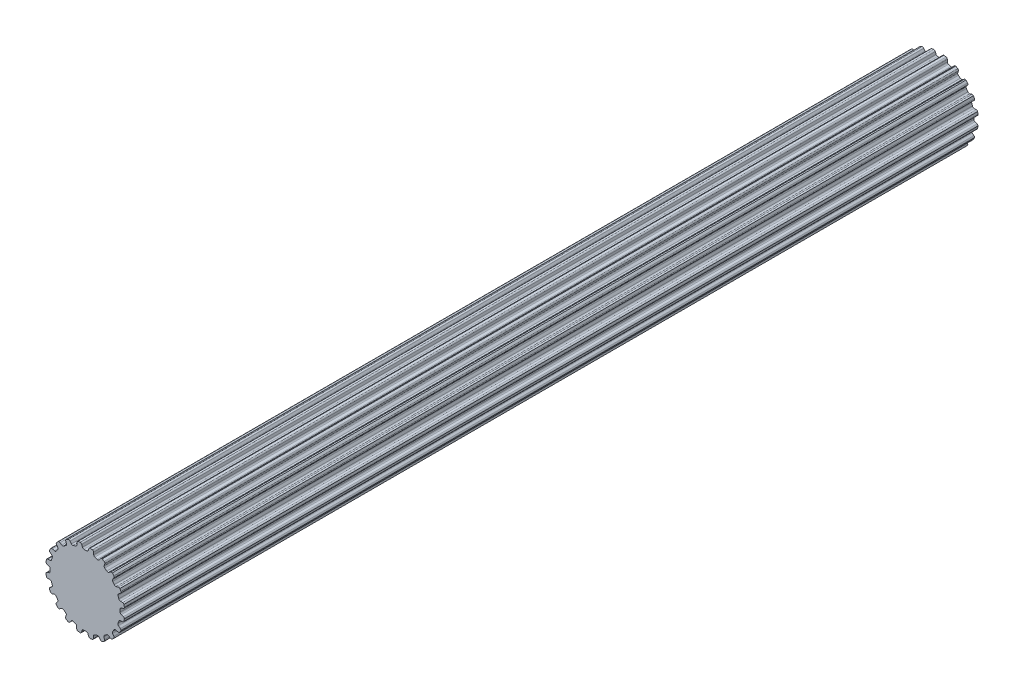
SolidWorks part; units mm, degrees
ref_plane "Front Plane" through (0, 0, 0) normal (0, 0, 1) x (1, 0, 0)
ref_plane "Top Plane" through (0, 0, 0) normal (0, 1, 0) x (1, 0, 0)
ref_plane "Right Plane" through (0, 0, 0) normal (1, 0, 0) x (0, 0, -1)
sketch "Sketch1" plane through (0, 0, 0) normal (0, 0, 1) x (1, 0, 0)
  line L0 (-0.1069, 2.9699) -> (0.1069, 2.9699)
  line L1 (0.3159, 3.2375) -> (0.2537, 3.0575)
  line L2 (-0.2964, 3.2367) -> (-0.2318, 3.0575)
  line L3 (-0.2964, 3.2367) -> (0.3159, 3.2375) construction
  line L4 (0, 3.3252) -> (0, 0) construction
  line L5 (-0.2318, 3.0575) -> (0.2537, 3.0575) construction
  line L6 (-0.4281, 3.3241) -> (0.4281, 3.3263) construction
  line L7 (0.7183, 3.1698) -> (0.7244, 2.9795)
  line L8 (0.816, 2.8576) -> (1.0195, 2.7915)
  line L9 (1.3009, 2.9815) -> (1.1862, 2.8295)
  line L10 (1.6627, 2.7927) -> (1.6097, 2.6099)
  line L11 (1.6591, 2.4655) -> (1.8322, 2.3398)
  line L12 (2.1585, 2.4335) -> (2.0025, 2.3245)
  line L13 (2.4443, 2.1423) -> (2.3374, 1.9847)
  line L14 (2.3398, 1.8322) -> (2.4655, 1.6591)
  line L15 (2.8049, 1.6474) -> (2.6228, 1.5919)
  line L16 (2.9866, 1.2821) -> (2.8363, 1.1653)
  line L17 (2.7915, 1.0195) -> (2.8576, 0.816)
  line L18 (3.1767, 0.7) -> (2.9863, 0.7035)
  line L19 (3.2367, 0.2964) -> (3.0575, 0.2318)
  line L20 (2.9699, 0.1069) -> (2.9699, -0.1069)
  line L21 (3.2375, -0.3159) -> (3.0575, -0.2537)
  line L22 (3.1698, -0.7183) -> (2.9795, -0.7244)
  line L23 (2.8576, -0.816) -> (2.7915, -1.0195)
  line L24 (2.9815, -1.3009) -> (2.8295, -1.1862)
  line L25 (2.7927, -1.6627) -> (2.6099, -1.6097)
  line L26 (2.4655, -1.6591) -> (2.3398, -1.8322)
  line L27 (2.4335, -2.1585) -> (2.3245, -2.0025)
  line L28 (2.1423, -2.4443) -> (1.9847, -2.3374)
  line L29 (1.8322, -2.3398) -> (1.6591, -2.4655)
  line L30 (1.6474, -2.8049) -> (1.5919, -2.6228)
  line L31 (1.2821, -2.9866) -> (1.1653, -2.8363)
  line L32 (1.0195, -2.7915) -> (0.816, -2.8576)
  line L33 (0.7, -3.1767) -> (0.7035, -2.9863)
  line L34 (0.2964, -3.2367) -> (0.2318, -3.0575)
  line L35 (0.1069, -2.9699) -> (-0.1069, -2.9699)
  line L36 (-0.3159, -3.2375) -> (-0.2537, -3.0575)
  line L37 (-0.7183, -3.1698) -> (-0.7244, -2.9795)
  line L38 (-0.816, -2.8576) -> (-1.0195, -2.7915)
  line L39 (-1.3009, -2.9815) -> (-1.1862, -2.8295)
  line L40 (-1.6627, -2.7927) -> (-1.6097, -2.6099)
  line L41 (-1.6591, -2.4655) -> (-1.8322, -2.3398)
  line L42 (-2.1585, -2.4335) -> (-2.0025, -2.3245)
  line L43 (-2.4443, -2.1423) -> (-2.3374, -1.9847)
  line L44 (-2.3398, -1.8322) -> (-2.4655, -1.6591)
  line L45 (-2.8049, -1.6474) -> (-2.6228, -1.5919)
  line L46 (-2.9866, -1.2821) -> (-2.8363, -1.1653)
  line L47 (-2.7915, -1.0195) -> (-2.8576, -0.816)
  line L48 (-3.1767, -0.7) -> (-2.9863, -0.7035)
  line L49 (-3.2367, -0.2964) -> (-3.0575, -0.2318)
  line L50 (-2.9699, -0.1069) -> (-2.9699, 0.1069)
  line L51 (-3.2375, 0.3159) -> (-3.0575, 0.2537)
  line L52 (-3.1698, 0.7183) -> (-2.9795, 0.7244)
  line L53 (-2.8576, 0.816) -> (-2.7915, 1.0195)
  line L54 (-2.9815, 1.3009) -> (-2.8295, 1.1862)
  line L55 (-2.7927, 1.6627) -> (-2.6099, 1.6097)
  line L56 (-2.4655, 1.6591) -> (-2.3398, 1.8322)
  line L57 (-2.4335, 2.1585) -> (-2.3245, 2.0025)
  line L58 (-2.1423, 2.4443) -> (-1.9847, 2.3374)
  line L59 (-1.8322, 2.3398) -> (-1.6591, 2.4655)
  line L60 (-1.6474, 2.8049) -> (-1.5919, 2.6228)
  line L61 (-1.2821, 2.9866) -> (-1.1653, 2.8363)
  line L62 (-1.0195, 2.7915) -> (-0.816, 2.8576)
  line L63 (-0.7, 3.1767) -> (-0.7035, 2.9863)
  line L64 (0.4281, 3.3263) -> (0.62, 3.2938)
  line L65 (1.4351, 3.0312) -> (1.6075, 2.9409)
  line L66 (2.3015, 2.4394) -> (2.4376, 2.3003)
  line L67 (2.9427, 1.6088) -> (3.0291, 1.4344)
  line L68 (3.2958, 0.6207) -> (3.3241, 0.4281)
  line L69 (3.3263, -0.4281) -> (3.2938, -0.62)
  line L70 (3.0312, -1.4351) -> (2.9409, -1.6075)
  line L71 (2.4394, -2.3015) -> (2.3003, -2.4376)
  line L72 (1.6088, -2.9427) -> (1.4344, -3.0291)
  line L73 (0.6207, -3.2958) -> (0.4281, -3.3241)
  line L74 (-0.4281, -3.3263) -> (-0.62, -3.2938)
  line L75 (-1.4351, -3.0312) -> (-1.6075, -2.9409)
  line L76 (-2.3015, -2.4394) -> (-2.4376, -2.3003)
  line L77 (-2.9427, -1.6088) -> (-3.0291, -1.4344)
  line L78 (-3.2958, -0.6207) -> (-3.3241, -0.4281)
  line L79 (-3.3263, 0.4281) -> (-3.2938, 0.62)
  line L80 (-3.0312, 1.4351) -> (-2.9409, 1.6075)
  line L81 (-2.4394, 2.3015) -> (-2.3003, 2.4376)
  line L82 (-1.6088, 2.9427) -> (-1.4344, 3.0291)
  line L83 (-0.6207, 3.2958) -> (-0.4281, 3.3241)
  arc A0 (0.2537, 3.0575) -> (0.1069, 2.9699) centre (0.1283, 3.1009) cw
  arc A1 (-0.2318, 3.0575) -> (-0.1069, 2.9699) centre (-0.1069, 3.1026) ccw
  arc A2 (0.62, 3.2938) -> (0.7183, 3.1698) centre (0.5856, 3.1656) cw
  arc A3 (0.7244, 2.9795) -> (0.816, 2.8576) centre (0.857, 2.9838) ccw
  arc A4 (-0.4281, 3.3241) -> (-0.2964, 3.2367) centre (-0.4213, 3.1916) cw
  arc A5 (0.4281, 3.3263) -> (0.3159, 3.2375) centre (0.4413, 3.1942) ccw
  arc A6 (1.1862, 2.8295) -> (1.0195, 2.7915) centre (1.0802, 2.9095) cw
  arc A7 (1.4351, 3.0312) -> (1.3009, 2.9815) centre (1.4068, 2.9015) ccw
  arc A8 (1.6075, 2.9409) -> (1.6627, 2.7927) centre (1.5352, 2.8297) cw
  arc A9 (1.6097, 2.6099) -> (1.6591, 2.4655) centre (1.7371, 2.5729) ccw
  arc A10 (2.0025, 2.3245) -> (1.8322, 2.3398) centre (1.9264, 2.4332) cw
  arc A11 (2.3015, 2.4394) -> (2.1585, 2.4335) centre (2.2346, 2.3248) ccw
  arc A12 (2.4376, 2.3003) -> (2.4443, 2.1423) centre (2.3345, 2.2168) cw
  arc A13 (2.3374, 1.9847) -> (2.3398, 1.8322) centre (2.4472, 1.9102) ccw
  arc A14 (2.6228, 1.5919) -> (2.4655, 1.6591) centre (2.5841, 1.7189) cw
  arc A15 (2.9427, 1.6088) -> (2.8049, 1.6474) centre (2.8436, 1.5205) ccw
  arc A16 (3.0291, 1.4344) -> (2.9866, 1.2821) centre (2.9052, 1.3869) cw
  arc A17 (2.8363, 1.1653) -> (2.7915, 1.0195) centre (2.9177, 1.0605) ccw
  arc A18 (2.9863, 0.7035) -> (2.8576, 0.816) centre (2.9887, 0.8362) cw
  arc A19 (3.2958, 0.6207) -> (3.1767, 0.7) centre (3.1743, 0.5673) ccw
  arc A20 (3.3241, 0.4281) -> (3.2367, 0.2964) centre (3.1916, 0.4213) cw
  arc A21 (3.0575, 0.2318) -> (2.9699, 0.1069) centre (3.1026, 0.1069) ccw
  arc A22 (3.0575, -0.2537) -> (2.9699, -0.1069) centre (3.1009, -0.1283) cw
  arc A23 (3.3263, -0.4281) -> (3.2375, -0.3159) centre (3.1942, -0.4413) ccw
  arc A24 (3.2938, -0.62) -> (3.1698, -0.7183) centre (3.1656, -0.5856) cw
  arc A25 (2.9795, -0.7244) -> (2.8576, -0.816) centre (2.9838, -0.857) ccw
  arc A26 (2.8295, -1.1862) -> (2.7915, -1.0195) centre (2.9095, -1.0802) cw
  arc A27 (3.0312, -1.4351) -> (2.9815, -1.3009) centre (2.9015, -1.4068) ccw
  arc A28 (2.9409, -1.6075) -> (2.7927, -1.6627) centre (2.8297, -1.5352) cw
  arc A29 (2.6099, -1.6097) -> (2.4655, -1.6591) centre (2.5729, -1.7371) ccw
  arc A30 (2.3245, -2.0025) -> (2.3398, -1.8322) centre (2.4332, -1.9264) cw
  arc A31 (2.4394, -2.3015) -> (2.4335, -2.1585) centre (2.3248, -2.2346) ccw
  arc A32 (2.3003, -2.4376) -> (2.1423, -2.4443) centre (2.2168, -2.3345) cw
  arc A33 (1.9847, -2.3374) -> (1.8322, -2.3398) centre (1.9102, -2.4472) ccw
  arc A34 (1.5919, -2.6228) -> (1.6591, -2.4655) centre (1.7189, -2.5841) cw
  arc A35 (1.6088, -2.9427) -> (1.6474, -2.8049) centre (1.5205, -2.8436) ccw
  arc A36 (1.4344, -3.0291) -> (1.2821, -2.9866) centre (1.3869, -2.9052) cw
  arc A37 (1.1653, -2.8363) -> (1.0195, -2.7915) centre (1.0605, -2.9177) ccw
  arc A38 (0.7035, -2.9863) -> (0.816, -2.8576) centre (0.8362, -2.9887) cw
  arc A39 (0.6207, -3.2958) -> (0.7, -3.1767) centre (0.5673, -3.1743) ccw
  arc A40 (0.4281, -3.3241) -> (0.2964, -3.2367) centre (0.4213, -3.1916) cw
  arc A41 (0.2318, -3.0575) -> (0.1069, -2.9699) centre (0.1069, -3.1026) ccw
  arc A42 (-0.2537, -3.0575) -> (-0.1069, -2.9699) centre (-0.1283, -3.1009) cw
  arc A43 (-0.4281, -3.3263) -> (-0.3159, -3.2375) centre (-0.4413, -3.1942) ccw
  arc A44 (-0.62, -3.2938) -> (-0.7183, -3.1698) centre (-0.5856, -3.1656) cw
  arc A45 (-0.7244, -2.9795) -> (-0.816, -2.8576) centre (-0.857, -2.9838) ccw
  arc A46 (-1.1862, -2.8295) -> (-1.0195, -2.7915) centre (-1.0802, -2.9095) cw
  arc A47 (-1.4351, -3.0312) -> (-1.3009, -2.9815) centre (-1.4068, -2.9015) ccw
  arc A48 (-1.6075, -2.9409) -> (-1.6627, -2.7927) centre (-1.5352, -2.8297) cw
  arc A49 (-1.6097, -2.6099) -> (-1.6591, -2.4655) centre (-1.7371, -2.5729) ccw
  arc A50 (-2.0025, -2.3245) -> (-1.8322, -2.3398) centre (-1.9264, -2.4332) cw
  arc A51 (-2.3015, -2.4394) -> (-2.1585, -2.4335) centre (-2.2346, -2.3248) ccw
  arc A52 (-2.4376, -2.3003) -> (-2.4443, -2.1423) centre (-2.3345, -2.2168) cw
  arc A53 (-2.3374, -1.9847) -> (-2.3398, -1.8322) centre (-2.4472, -1.9102) ccw
  arc A54 (-2.6228, -1.5919) -> (-2.4655, -1.6591) centre (-2.5841, -1.7189) cw
  arc A55 (-2.9427, -1.6088) -> (-2.8049, -1.6474) centre (-2.8436, -1.5205) ccw
  arc A56 (-3.0291, -1.4344) -> (-2.9866, -1.2821) centre (-2.9052, -1.3869) cw
  arc A57 (-2.8363, -1.1653) -> (-2.7915, -1.0195) centre (-2.9177, -1.0605) ccw
  arc A58 (-2.9863, -0.7035) -> (-2.8576, -0.816) centre (-2.9887, -0.8362) cw
  arc A59 (-3.2958, -0.6207) -> (-3.1767, -0.7) centre (-3.1743, -0.5673) ccw
  arc A60 (-3.3241, -0.4281) -> (-3.2367, -0.2964) centre (-3.1916, -0.4213) cw
  arc A61 (-3.0575, -0.2318) -> (-2.9699, -0.1069) centre (-3.1026, -0.1069) ccw
  arc A62 (-3.0575, 0.2537) -> (-2.9699, 0.1069) centre (-3.1009, 0.1283) cw
  arc A63 (-3.3263, 0.4281) -> (-3.2375, 0.3159) centre (-3.1942, 0.4413) ccw
  arc A64 (-3.2938, 0.62) -> (-3.1698, 0.7183) centre (-3.1656, 0.5856) cw
  arc A65 (-2.9795, 0.7244) -> (-2.8576, 0.816) centre (-2.9838, 0.857) ccw
  arc A66 (-2.8295, 1.1862) -> (-2.7915, 1.0195) centre (-2.9095, 1.0802) cw
  arc A67 (-3.0312, 1.4351) -> (-2.9815, 1.3009) centre (-2.9015, 1.4068) ccw
  arc A68 (-2.9409, 1.6075) -> (-2.7927, 1.6627) centre (-2.8297, 1.5352) cw
  arc A69 (-2.6099, 1.6097) -> (-2.4655, 1.6591) centre (-2.5729, 1.7371) ccw
  arc A70 (-2.3245, 2.0025) -> (-2.3398, 1.8322) centre (-2.4332, 1.9264) cw
  arc A71 (-2.4394, 2.3015) -> (-2.4335, 2.1585) centre (-2.3248, 2.2346) ccw
  arc A72 (-2.3003, 2.4376) -> (-2.1423, 2.4443) centre (-2.2168, 2.3345) cw
  arc A73 (-1.9847, 2.3374) -> (-1.8322, 2.3398) centre (-1.9102, 2.4472) ccw
  arc A74 (-1.5919, 2.6228) -> (-1.6591, 2.4655) centre (-1.7189, 2.5841) cw
  arc A75 (-1.6088, 2.9427) -> (-1.6474, 2.8049) centre (-1.5205, 2.8436) ccw
  arc A76 (-1.4344, 3.0291) -> (-1.2821, 2.9866) centre (-1.3869, 2.9052) cw
  arc A77 (-1.1653, 2.8363) -> (-1.0195, 2.7915) centre (-1.0605, 2.9177) ccw
  arc A78 (-0.7035, 2.9863) -> (-0.816, 2.8576) centre (-0.8362, 2.9887) cw
  arc A79 (-0.6207, 3.2958) -> (-0.7, 3.1767) centre (-0.5673, 3.1743) ccw
  point P14 (0, 2.9699)
  point P247 (0, 0)
  dimension "D4" = 0.1327
  dimension "D8" = 20
  dimension "D1" = 2.9699
  dimension "D2" = 0.2139
  dimension "D3" = 0.1904
  dimension "D5" = 0.0877
  dimension "D6" = 0.4855
  dimension "D7" = 0.8563
extrude "Boss-Extrude1" add sketch "Sketch1" along normal mid plane 72.4611
sketch "Sketch2" plane through (0, 0, 36.2306) normal (0, 0, 1) x (1, 0, 0)
  circle A0 centre (0, 0) radius 3.3516 construction
sketch "Sketch3" plane through (0, 0, -36.2306) normal (0, 0, -1) x (-1, 0, 0)
  circle A0 centre (0, 0) radius 3.3516 construction
  circle A1 centre (0, 0) radius 3.3516 construction
